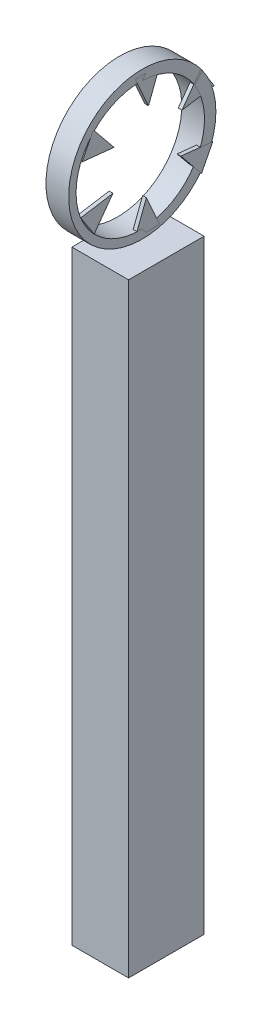
SolidWorks part; units mm, degrees
ref_plane "Front Plane" through (0, 0, 0) normal (0, 0, 1) x (1, 0, 0)
ref_plane "Top Plane" through (0, 0, 0) normal (0, 1, 0) x (1, 0, 0)
ref_plane "Right Plane" through (0, 0, 0) normal (1, 0, 0) x (0, 0, -1)
sketch "Sketch1" plane through (0, 0, 0) normal (0, 0, 1) x (1, 0, 0)
  line L1 (0, 0) -> (19.05, 0)
  line L2 (0, 0) -> (0, -203.2)
  line L3 (0, -203.2) -> (19.05, -203.2)
  line L4 (19.05, 0) -> (19.05, -203.2)
  line L5 (0, 0) -> (19.05, -203.2) construction
  line L6 (0, -203.2) -> (19.05, 0) construction
  point P4 (9.525, -101.6)
  dimension "D1" = 203.2
  dimension "D2" = 19.05
extrude "Boss-Extrude1" add sketch "Sketch1" along normal blind 25.4
ref_plane "Plane1" through (9.525, 0, 0) normal (-1, 0, 0) x (0, 0, 1)
sketch "Sketch3" plane through (9.525, 0, 0) normal (-1, 0, 0) x (0, 0, 1)
  circle A0 centre (11.2668, 24.7433) radius 24.7433
  circle A1 centre (11.2668, 24.7433) radius 23.1154
  point P24 (11.2668, 24.7433)
extrude "Boss-Extrude2" add sketch "Sketch3" along normal blind 7.62 separate body contours A0
sketch "Sketch4" plane through (1.905, 0, 0) normal (-1, 0, 0) x (0, 0, 1)
  circle A0 centre (11.9438, 24.5718) radius 21.5787
extrude "Cut-Extrude1" cut sketch "Sketch4" against normal blind 25.4
sketch "Sketch5" plane through (9.525, 0, 0) normal (-1, 0, 0) x (0, 0, 1)
  line L0 (31.9732, 16.5427) -> (21.1188, 18.2849)
  line L1 (21.1188, 18.2849) -> (27.4366, 9.5513)
  line L2 (27.4366, 9.5513) -> (31.9732, 16.5427)
  line L3 (13.7957, 1.1166) -> (9.8773, 11.3878)
  line L4 (9.8773, 11.3878) -> (5.4726, 1.5497)
  line L5 (5.4726, 1.5497) -> (13.7957, 1.1166)
  line L6 (-8.6525, 9.1457) -> (-1.7165, 17.6747)
  line L7 (-1.7165, 17.6747) -> (-12.439, 16.5702)
  line L8 (-12.439, 16.5702) -> (-8.6525, 9.1457)
  line L9 (-12.9232, 32.6009) -> (-2.0688, 30.8587)
  line L10 (-2.0688, 30.8587) -> (-8.3866, 39.5924)
  line L11 (-8.3866, 39.5924) -> (-12.9232, 32.6009)
  line L12 (5.2543, 48.0271) -> (9.1727, 37.7558)
  line L13 (9.1727, 37.7558) -> (13.5774, 47.594)
  line L14 (13.5774, 47.594) -> (5.2543, 48.0271)
  line L15 (27.7025, 39.998) -> (20.7665, 31.4689)
  line L16 (20.7665, 31.4689) -> (31.489, 32.5735)
  line L17 (31.489, 32.5735) -> (27.7025, 39.998)
  circle A1 centre (11.9438, 24.5718) radius 21.5787 construction
  point P22 (9.525, 24.5718)
  dimension "D1" = 6
extrude "Boss-Extrude3" add sketch "Sketch5" along normal blind 1.27 separate body
